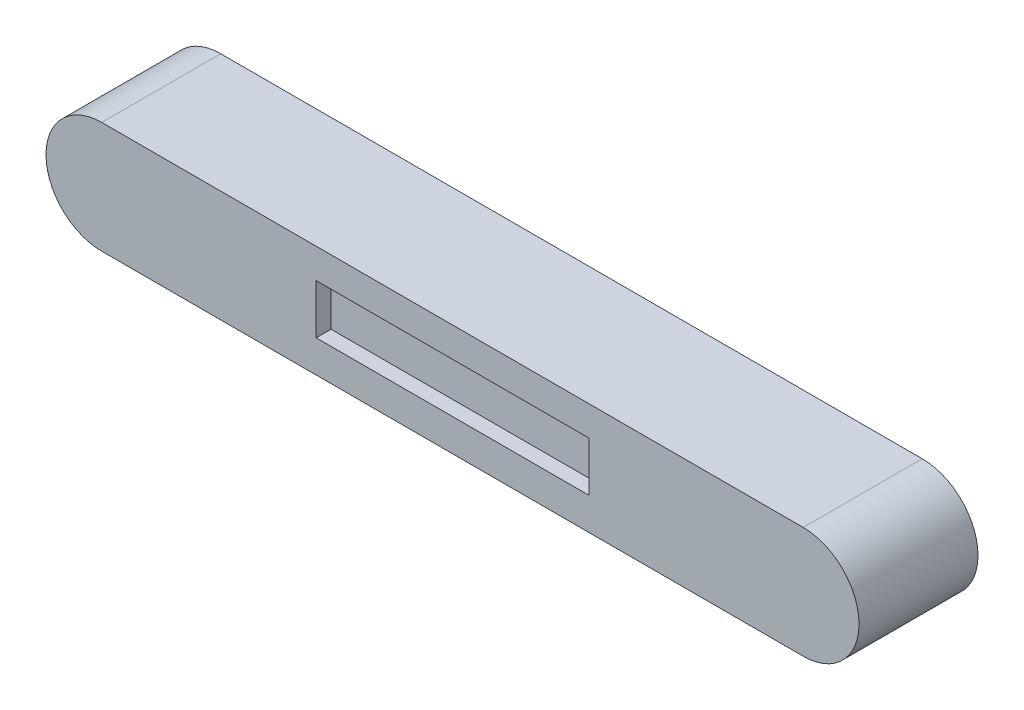
SolidWorks part; units mm, degrees
ref_plane "前视基准面" through (0, 0, 0) normal (0, 0, 1) x (1, 0, 0)
ref_plane "上视基准面" through (0, 0, 0) normal (0, 1, 0) x (1, 0, 0)
ref_plane "右视基准面" through (0, 0, 0) normal (1, 0, 0) x (0, 0, -1)
other "Configuration Table"
sketch "草图1" plane through (0, 0, 0) normal (0, 0, 1) x (1, 0, 0)
  line L1 (0, 0) -> (164, 0)
  line L2 (0, 0) -> (0, 22.5)
  line L3 (0, 22.5) -> (164, 22.5)
  line L4 (164, 0) -> (164, 22.5)
  dimension "D1" = 164
  dimension "D2" = 22.5
extrude "凸台-拉伸1" add sketch "草图1" along normal blind 24
sketch "草图2" plane through (0, 0, 24) normal (0, 0, 1) x (1, 0, 0)
  line L0 (0, 11.25) -> (164, 11.25) construction
  line L1 (0, 22.5) -> (0, 0) construction
  line L2 (164, 0) -> (164, 22.5) construction
  line L3 (164, 22.5) -> (0, 22.5) construction
  line L4 (82, 22.5) -> (82, 0) construction
  line L5 (0, 0) -> (164, 0) construction
  line L6 (11.25, 22.5) -> (0, 22.5)
  line L7 (0, 22.5) -> (0, 0)
  line L8 (0, 0) -> (11.25, 0)
  line L9 (152.75, 22.5) -> (164, 22.5)
  line L10 (164, 22.5) -> (164, 0)
  line L11 (164, 0) -> (152.75, 0)
  arc A0 (152.75, 0) -> (152.75, 22.5) centre (152.75, 11.25) ccw
  arc A1 (11.25, 0) -> (11.25, 22.5) centre (11.25, 11.25) cw
  line M4 (0, 22.5) -> (0, 0)
  line M5 (0, 0) -> (164, 0)
  line M6 (164, 0) -> (164, 22.5)
  line M7 (164, 22.5) -> (0, 22.5)
extrude "切除-拉伸1" cut sketch "草图2" against normal blind 24 contours A1 M4 M7 | A1 L7 M5 | A0 L10 M7 | A0 M5 M6
sketch "草图3" plane through (0, 0, 24) normal (0, 0, 1) x (1, 0, 0)
  line L0 (82, 60.1527) -> (82, -44.2711) construction
  line L1 (11.25, 0) -> (152.75, 0) construction
  line L2 (-22.3319, 11.5) -> (182.1035, 11.5) construction
  line L3 (54.5, 6.5) -> (109.5, 6.5)
  line L4 (54.5, 6.5) -> (54.5, 16.5)
  line L5 (54.5, 16.5) -> (109.5, 16.5)
  line L6 (109.5, 6.5) -> (109.5, 16.5)
  line L7 (54.5, 6.5) -> (109.5, 16.5) construction
  line L8 (54.5, 16.5) -> (109.5, 6.5) construction
  point P4 (82, 0)
  point P5 (82, 11.5)
  dimension "D1" = 11.5
  dimension "D2" = 55
  dimension "D3" = 10
extrude "切除-拉伸2" cut sketch "草图3" against normal blind 3
